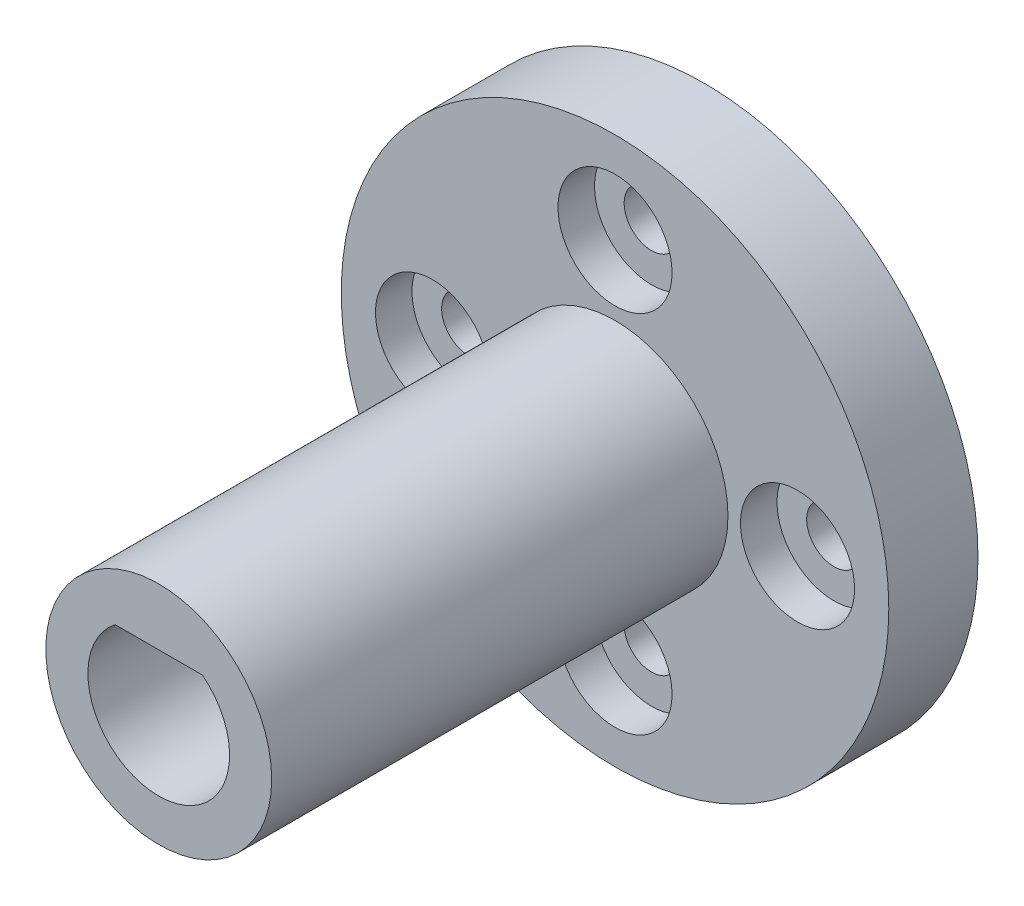
SolidWorks part; units mm, degrees
ref_plane "Plan de face" through (0, 0, 0) normal (0, 0, 1) x (1, 0, 0)
ref_plane "Plan de dessus" through (0, 0, 0) normal (0, 1, 0) x (1, 0, 0)
ref_plane "Plan de droite" through (0, 0, 0) normal (1, 0, 0) x (0, 0, -1)
sketch "Esquisse1" plane through (0, 0, 0) normal (0, 0, 1) x (1, 0, 0)
  circle A0 centre (0, 0) radius 12
  dimension "D1" = 24
extrude "Boss.-Extru.1" add sketch "Esquisse1" along normal blind 3.91
sketch "Esquisse6" plane through (0, 0, 0) normal (0, 0, -1) x (-1, 0, 0)
  circle A0 centre (0, 0) radius 4
  dimension "D1" = 8
extrude "Enlèv. mat.-Extru.2" cut sketch "Esquisse6" against normal blind 1.91
sketch "Esquisse7" plane through (0, 0, 3.91) normal (0, 0, 1) x (1, 0, 0)
  line L0 (1.9139, 2.445) -> (-1.9139, 2.445)
  line L1 (-5.4714, -3.105) -> (6.192, -3.105) construction
  arc A0 (-1.9139, 2.445) -> (1.9139, 2.445) centre (0, 0) ccw
  circle A1 centre (0, 0) radius 4.95
  dimension "D1" = 6.21
  dimension "D3" = 9.9
  dimension "D2" = 5.55
extrude "Boss.-Extru.2" add sketch "Esquisse7" along normal blind 20 contours A1 L1 A0 L0 | L1 A1
hole_wizard "Chambrage pour vis à tête ronde bombée M21" positions "Esquisse10" profile "Esquisse11" counterbore size "M2" standard "Ansi Metric" end condition through all
sketch "Esquisse10" plane through (0, 0, 3.91) normal (0, 0, 1) x (1, 0, 0)
  point P0 (0, 8)
  dimension "D1" = 8
sketch "Esquisse11" plane through (0, 8, 3.91) normal (1, 0, 0) x (0, -1, 0)
  line L0 (0, 0) -> (0, 3.91)
  line L1 (0, 3.91) -> (1.2, 3.91)
  line L3 (1.2, 3.91) -> (1.2, 1.6)
  line L4 (1.2, 1.6) -> (2.5, 1.6)
  line L5 (2.5, 1.6) -> (2.5, 0)
  line L7 (2.5, 0) -> (0, 0)
  line L11 (0, -6.35) -> (0, 107.95) construction
  dimension "Diamètre du perçage jusqu'au prochain" = 2.4
  dimension "Profondeur du perçage jusqu'au prochain" = 3.91
  dimension "Diamètre du chambrage" = 5
  dimension "Profondeur du chambrage" = 1.6
pattern_circular "Répétition circulaire2" count 4 every 90 about axis through (0, 0, 0) along (0, 0, 1) of "Chambrage pour vis à tête ronde bombée M21"
